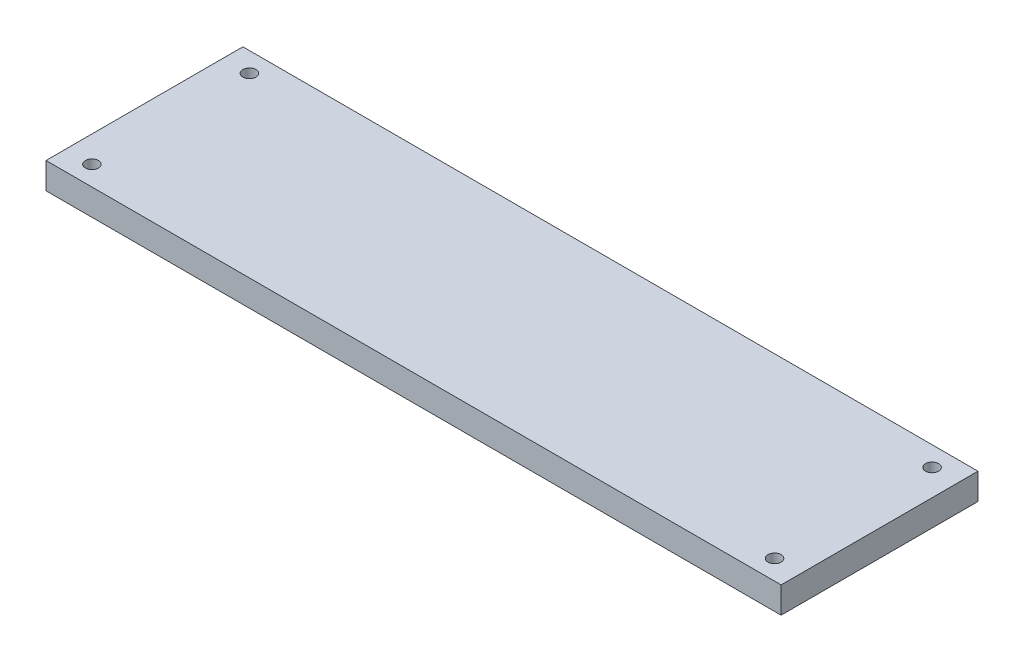
SolidWorks part; units mm, degrees
material "Oak"
ref_plane "Front Plane" through (0, 0, 0) normal (0, 0, 1) x (1, 0, 0)
ref_plane "Top Plane" through (0, 0, 0) normal (0, 1, 0) x (1, 0, 0)
ref_plane "Right Plane" through (0, 0, 0) normal (1, 0, 0) x (0, 0, -1)
sketch "Sketch1" plane through (0, 0, 0) normal (0, 1, 0) x (1, 0, 0)
  line L1 (-177.8, 47.625) -> (177.8, 47.625)
  line L2 (-177.8, 47.625) -> (-177.8, -47.625)
  line L3 (-177.8, -47.625) -> (177.8, -47.625)
  line L4 (177.8, 47.625) -> (177.8, -47.625)
  line L5 (-177.8, 47.625) -> (177.8, -47.625) construction
  line L6 (-177.8, -47.625) -> (177.8, 47.625) construction
  point P0 (0, 0)
  dimension "D1" = 95.25
  dimension "D2" = 355.6
extrude "Boss-Extrude1" add sketch "Sketch1" along normal blind 12.7
sketch "Sketch2" plane through (0, 12.7, 0) normal (0, 1, 0) x (1, 0, 0)
  line L0 (177.8, 47.625) -> (-177.8, 47.625) construction
  line L1 (177.8, -47.625) -> (177.8, 47.625) construction
  line L2 (0, -6.985) -> (0, 6.985) construction
  line L3 (-6.985, 0) -> (6.985, 0) construction
  circle A0 centre (165.1, 38.1) radius 3.175
  circle A1 centre (-165.1, 38.1) radius 3.175
  circle A2 centre (165.1, -38.1) radius 3.175
  circle A3 centre (-165.1, -38.1) radius 3.175
  dimension "D3" = 6.35
  dimension "D1" = 9.525
  dimension "D2" = 12.7
extrude "Cut-Extrude1" cut sketch "Sketch2" against normal through all
